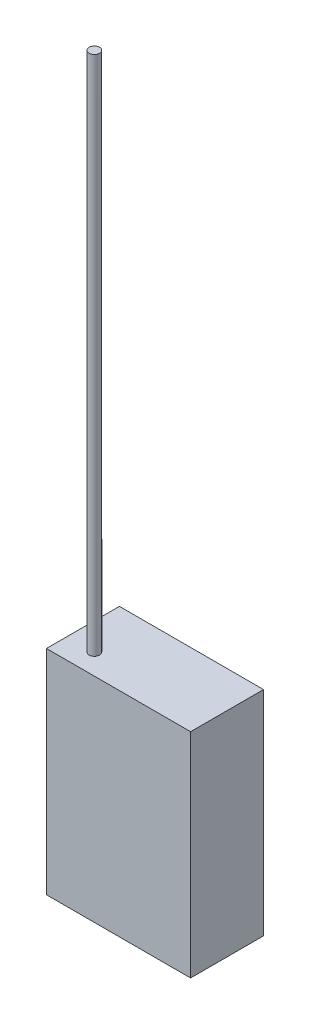
SolidWorks part; units mm, degrees
ref_plane "Front Plane" through (0, 0, 0) normal (0, 0, 1) x (1, 0, 0)
ref_plane "Top Plane" through (0, 0, 0) normal (0, 1, 0) x (1, 0, 0)
ref_plane "Right Plane" through (0, 0, 0) normal (1, 0, 0) x (0, 0, -1)
sketch "Sketch1" plane through (0, 0, 0) normal (0, 0, 1) x (1, 0, 0)
  line L1 (-63.0073, 12.0199) -> (-49.1804, 12.0199)
  line L2 (-63.0073, 12.0199) -> (-63.0073, -8.4439)
  line L3 (-63.0073, -8.4439) -> (-49.1804, -8.4439)
  line L4 (-49.1804, 12.0199) -> (-49.1804, -8.4439)
extrude "Boss-Extrude1" add sketch "Sketch1" along normal blind 7
sketch "Sketch2" plane through (0, 12.0199, 0) normal (0, 1, 0) x (1, 0, 0)
  line L0 (-84.7633, 0) -> (85.2367, 0) construction
  circle A0 centre (-60.4085, -5) radius 0.5
  dimension "D2" = 1
  dimension "D1" = 5
extrude "Boss-Extrude2" add sketch "Sketch2" along normal blind 50
